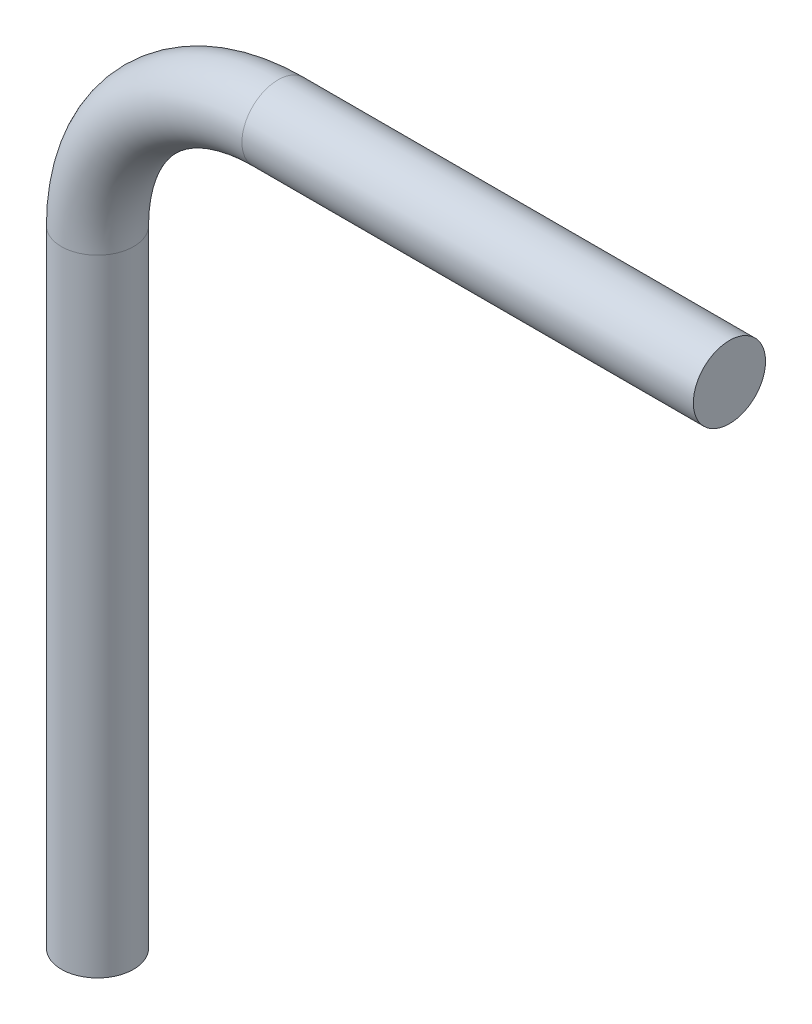
SolidWorks part; units mm, degrees
material "Copper"
ref_plane "Front Plane" through (0, 0, 0) normal (0, 0, 1) x (1, 0, 0)
ref_plane "Top Plane" through (0, 0, 0) normal (0, 1, 0) x (1, 0, 0)
ref_plane "Right Plane" through (0, 0, 0) normal (1, 0, 0) x (0, 0, -1)
sketch "Sketch1" plane through (0, 0, 0) normal (1, 0, 0) x (0, 0, -1)
  circle A0 centre (0, 0) radius 0.4
  dimension "D1" = 0.8
extrude "Boss-Extrude1" add sketch "Sketch1" along normal mid plane 5
sketch "Sketch2" plane through (0, 0, 0) normal (0, 0, 1) x (1, 0, 0)
  line L0 (-2.5, 0.4) -> (-2.5, -0.4) construction
  line L1 (-4.5, -2) -> (-4.5, -8.9334)
  arc A0 (-2.5, 0) -> (-4.5, -2) centre (-2.5, -2) ccw
  point P3 (0, 0)
  dimension "D1" = 2
  dimension "D2" = 6.9334
sweep "Sweep1" add path "Sketch2" circular profile diameter 0.8 parameters "D3"=0.8
